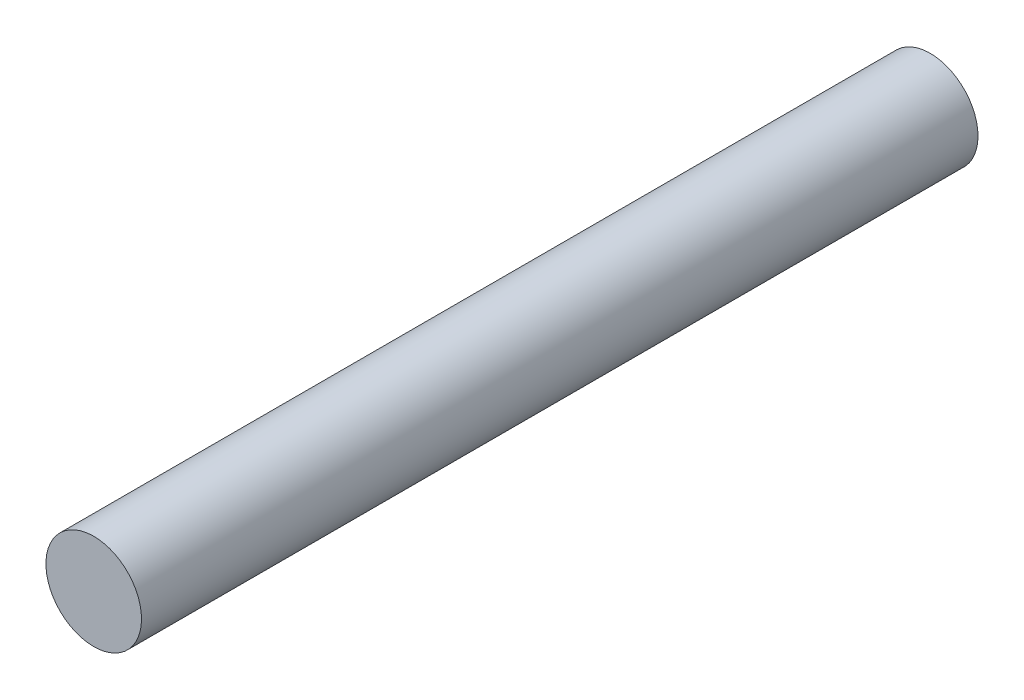
SolidWorks part; units mm, degrees
material "不锈钢"
ref_plane "前视基准面" through (0, 0, 0) normal (0, 0, 1) x (1, 0, 0)
ref_plane "上视基准面" through (0, 0, 0) normal (0, 1, 0) x (1, 0, 0)
ref_plane "右视基准面" through (0, 0, 0) normal (1, 0, 0) x (0, 0, -1)
sketch "草图1" plane through (0, 0, 0) normal (0, 0, 1) x (1, 0, 0)
  circle A0 centre (0, 0) radius 1
  dimension "D1" = 2
extrude "凸台-拉伸1" add sketch "草图1" along normal blind 17.5
